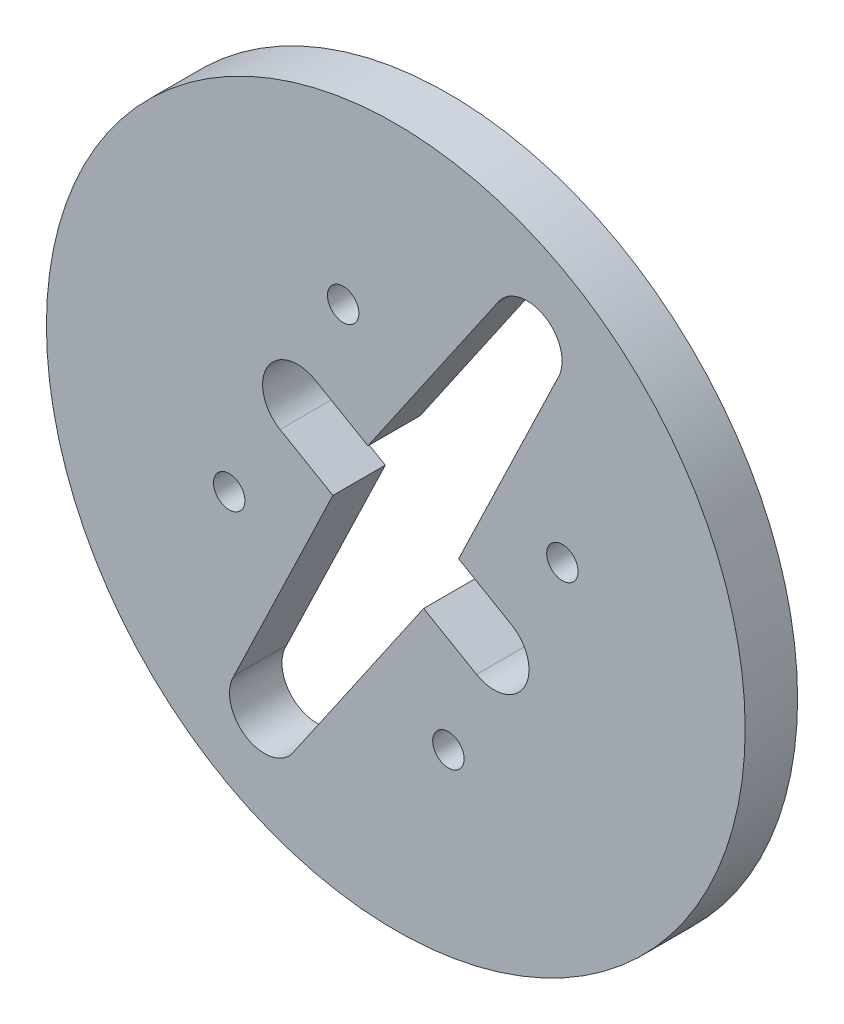
SolidWorks part; units mm, degrees
ref_plane "Front Plane" through (0, 0, 0) normal (0, 0, 1) x (1, 0, 0)
ref_plane "Top Plane" through (0, 0, 0) normal (0, 1, 0) x (1, 0, 0)
ref_plane "Right Plane" through (0, 0, 0) normal (1, 0, 0) x (0, 0, -1)
sketch "Sketch1" plane through (0, 0, 0) normal (0, 0, 1) x (1, 0, 0)
  line L0 (-5.6246, 3.258) -> (5.6246, -3.258) construction
  line L1 (-4.6221, 4.9886) -> (6.627, -1.5273)
  line L2 (-6.627, 1.5273) -> (4.6221, -4.9886)
  line L3 (3.5984, 0.227) -> (-1.5935, 3.2343)
  line L4 (1.0025, 1.7306) -> (7.5184, 12.9797) construction
  line L5 (5.7878, 13.9822) -> (9.249, 11.9773)
  line L6 (-1.5935, 3.2343) -> (5.7878, 13.9822)
  line L7 (3.5984, 0.227) -> (9.249, 11.9773)
  line L8 (-5.6246, 3.258) -> (5.6246, -3.258)
  line L9 (1.5935, -3.2343) -> (-3.5984, -0.227)
  line L10 (-3.5984, -0.227) -> (-9.249, -11.9773)
  line L11 (-9.249, -11.9773) -> (-5.7878, -13.9822)
  line L12 (1.5935, -3.2343) -> (-5.7878, -13.9822)
  circle A0 centre (0, 0) radius 20
  arc A1 (-4.6221, 4.9886) -> (-6.627, 1.5273) centre (-5.6246, 3.258) ccw
  arc A2 (4.6221, -4.9886) -> (6.627, -1.5273) centre (5.6246, -3.258) ccw
  circle A3 centre (7.5184, 12.9797) radius 2
  circle A4 centre (-7.5184, -12.9797) radius 2
  point P5 (0, 0)
  point P14 (1.0025, 1.7306)
  point P18 (7.5184, 12.9797)
  point P22 (0, 0)
  dimension "D1" = 13
  dimension "D2" = 6
  dimension "D3" = 13
  dimension "D4" = 4
extrude "Boss-Extrude1" add sketch "Sketch1" along normal blind 3 contours A0 L12 A4 L10 L2 A1 L1 L6 A3 L7 A2
sketch "Sketch2" plane through (0, 0, 0) normal (0, 0, -1) x (-1, 0, 0)
  line L0 (0, 0) -> (-3.0112, -9.5359) construction
  circle A0 centre (-3.0112, -9.5359) radius 0.9
  circle A1 centre (-9.5359, 3.0112) radius 0.9
  circle A2 centre (3.0112, 9.5359) radius 0.9
  circle A3 centre (9.5359, -3.0112) radius 0.9
  point P13 (0, 0)
  dimension "D2" = 4
  dimension "D1" = 10
extrude "Cut-Extrude1" cut sketch "Sketch2" against normal blind 3
